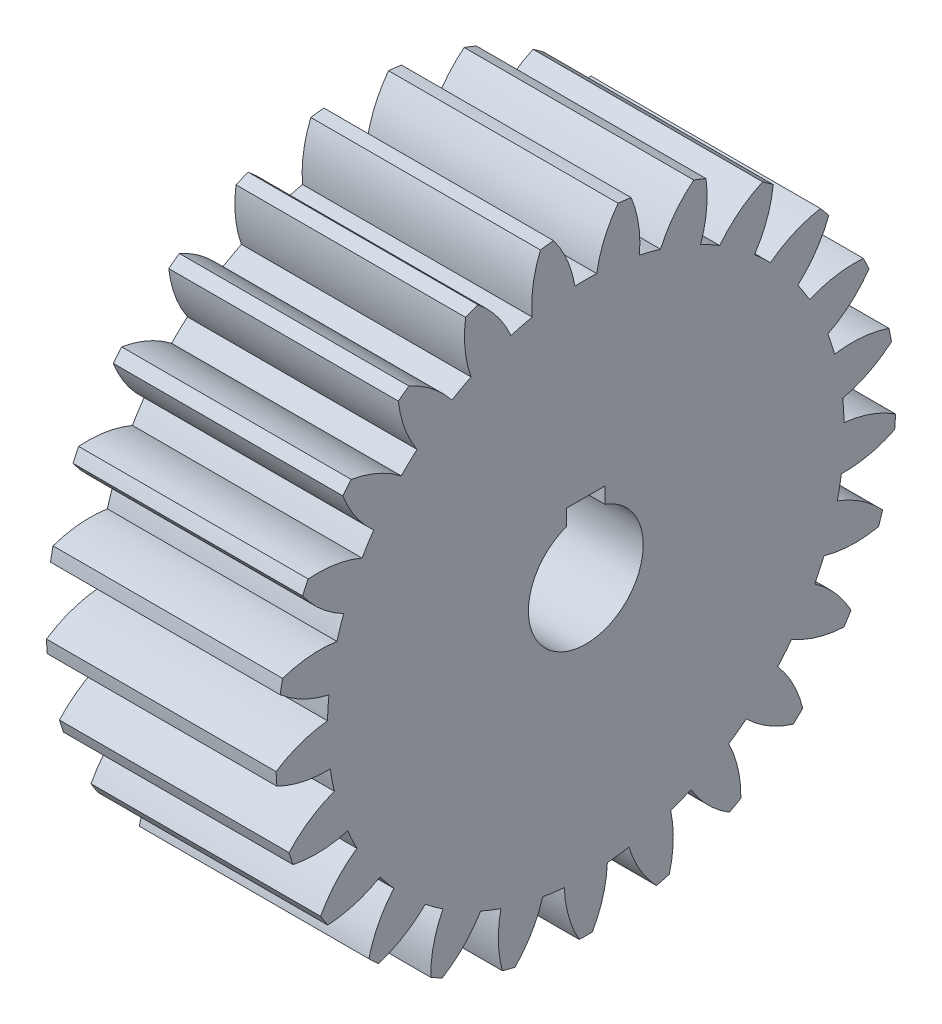
SolidWorks part; units mm, degrees
ref_plane "Plane1" through (0, 0, 0) normal (0, 0, 1) x (1, 0, 0)
ref_plane "Plane2" through (0, 0, 0) normal (0, 1, 0) x (1, 0, 0)
ref_plane "Plane3" through (0, 0, 0) normal (1, 0, 0) x (0, 0, -1)
other "Configuration Table"
sketch "HoldingSke" plane through (0, 0, 0) normal (0, 1, 0) x (1, 0, 0)
  line L0 (0, 0) -> (0.1511, -0.0704)
  line L1 (-15, 0) -> (100, 0) construction
  line L2 (0, 0) -> (-2.1039, 2.3779)
  line L3 (0, 0) -> (-11.863, 4.5341)
  line L4 (0, 0) -> (7.8269, 3.6497)
  line L5 (0, 0) -> (-46.8476, -17.4728)
  line L6 (0, 0) -> (-49.7378, -33.5582)
  line L7 (-2.1039, 2.3779) -> (10.8111, 60.9715)
  line L8 (-76.2, 54.61) -> (-72.9, 54.61)
  line L9 (-71.009, 38.7566) -> (-53.1078, 45.2721)
  line L10 (-76.2, 71.12) -> (104.1128, 71.12)
  line L11 (0, 0) -> (-60, 0)
  line L12 (-76.2, 101.6) -> (-75.993, 101.6)
  line L13 (24.9733, 27.94) -> (52.9518, 28.4284)
  line L14 (24.9733, 27.94) -> (24.9743, 27.94)
  line L15 (24.9733, 27.94) -> (100.4006, 29.5858)
  line L16 (-63.627, -6) -> (-12.827, -6)
  circle A0 centre (0, 0) radius 15
  circle A1 centre (0, 0) radius 37.5
  circle A2 centre (0, 0) radius 37.5
  circle A3 centre (0, 0) radius 15
  dimension "MHD" = 75
  dimension "Hub_dia" = 75
  dimension "Pitch" = 0.1667
  dimension "Overall_len" = 50
  dimension "Thickness" = 60
  dimension "OAL" = 60.0001
  dimension "T_dim" = 3.3
  dimension "Ap" = 20
  dimension "H" = 19.05
  dimension "Pitch_radius" = 180.3128
  dimension "Width" = 60
  dimension "Backlash" = 0.207
  dimension "Addendum_fac" = 1
  dimension "Dedendum_fac" = 1.25
  dimension "Clearance_fac" = 0.25
  dimension "Dedendum_add" = 0.001
  dimension "Module" = 6
sketch "BasProSke" plane through (0, 0, 0) normal (0, 1, 0) x (1, 0, 0)
  line L0 (-10, 0) -> (60, 0) construction
  line L1 (0, 0) -> (0, 81)
  line L2 (0, 0) -> (60, 0)
  line L3 (60, 0) -> (60, 81)
  line L4 (60, 81) -> (0, 81)
  dimension "Thickness" = 60
revolve "Base-Revolve" add sketch "BasProSke" angle 360 about L0
sketch "TooCutSke" plane through (0, 0, 0) normal (1, 0, 0) x (0, 0, -1)
  line L1 (0, 0) -> (0, 107) construction
  line L2 (0, 0) -> (-5.0714, 74.8283) construction
  line L3 (0, 0) -> (-18.7684, 148.567) construction
  line L4 (-5.0714, 74.8283) -> (-9.3842, 74.2835) construction
  arc A0 (2.8482, 67.4389) -> (-2.8482, 67.4389) centre (0, 0) ccw
  arc A1 (8.4641, 80.5821) -> (-8.4641, 80.5821) centre (0, 0) ccw
  circle A2 centre (0, 0) radius 75 construction
  circle A3 centre (0, 0) radius 70.4769 construction
  arc A4 (-2.8482, 67.4389) -> (-8.4641, 80.5821) centre (-32.4493, 62.5623) ccw
  arc A5 (8.4641, 80.5821) -> (2.8482, 67.4389) centre (32.4493, 62.5623) ccw
  dimension "Half_CT" = 4.347
extrude "ToothCut" cut sketch "TooCutSke" along normal through all
fillet "Breaks" [suppressed] radius 0.12
fillet "RootFillets" [suppressed] radius 1.501
pattern_circular "TeethCuts" count 25 every 14.4 about axis through (-10, 0, 0) along (1, 0, 0) of "ToothCut", "RootFillets", "Breaks"
sketch "HubNeaOneSke" plane through (0, 0, 0) normal (-1, 0, 0) x (0, 0, 1)
  circle A0 centre (0, 0) radius 37.5
  dimension "Diameter" = 75
extrude "HubNearOne" [suppressed] add sketch "HubNeaOneSke" along normal blind 10.0001
sketch "HubNeaBotSke" plane through (0, 0, 0) normal (-1, 0, 0) x (0, 0, 1)
  circle A0 centre (0, 0) radius 37.5
  dimension "Diameter" = 75
extrude "HubNearBoth" [suppressed] add sketch "HubNeaBotSke" along normal blind 5
ref_plane "FarPln" through (60, 0, 0) normal (1, 0, 0) x (0, 0, -1)
sketch "HubFarSke" plane through (60, 0, 0) normal (1, 0, 0) x (0, 0, -1)
  circle A0 centre (0, 0) radius 37.5
  dimension "Diameter" = 75
extrude "HubFar" [suppressed] add sketch "HubFarSke" along normal blind 5
sketch "BorSke" plane through (0, 0, 0) normal (1, 0, 0) x (0, 0, -1)
  circle A0 centre (0, 0) radius 15
extrude "Bore" cut sketch "BorSke" along normal mid plane 120.0001
sketch "KeySke" plane through (0, 0, 0) normal (1, 0, 0) x (0, 0, -1)
  line L0 (-5, 0) -> (-5, 18.3)
  line L1 (-5, 18.3) -> (5, 18.3)
  line L2 (5, 18.3) -> (5, 0)
  line L3 (0, 0) -> (0, 34) construction
  line L4 (-5, 0) -> (5, 0)
extrude "Keyway" cut sketch "KeySke" along normal mid plane 120.0001
pattern_circular "Keyway2" [suppressed] count 2 every 90 about axis through (-10, 0, 0) along (1, 0, 0)
equation "' \"Module@HoldingSke\" = 6.35"
equation "' \"Num_teeth@HoldingSke\" = 12"
equation "' \"Ap@HoldingSke\" =  20"
equation "' \"Ap@HoldingSke\" = 20"
equation "' \"Width@HoldingSke\" = 0.5 * 25.4"
equation "' \"Hub_dia@HoldingSke\"= 1 * 25.4"
equation "' \"Hub_dia@HoldingSke\" = 1 * 25.4"
equation "' \"Overall_len@HoldingSke\" = 1.0 * 25.4"
equation "' \"Bore@HoldingSke\" = 0.75 * 25.4"
equation "' \"T_dim@HoldingSke\" = 0.1 * 25.4"
equation "' \"Width@KeySke\" = 0.25 * 25.4"
equation "' \"Show_teeth@HoldingSke\" = 13"
equation "' \"Backlash@HoldingSke\" = 0.009 * 25.4"
equation "' \"Addendum_fac@HoldingSke\" = 1.0"
equation "' \"Dedendum_fac@HoldingSke\" = 1.25"
equation "' \"Dedendum_add@HoldingSke\" = 0.00005 * 25.4"
equation "' \"Clearance_fac@HoldingSke\" = 0.25"
equation "\"Pitch@HoldingSke\" = 1 / \"Module@HoldingSke\""
equation "\"Overcut_dia@TooCutSke\" = (\"Num_teeth@HoldingSke\" + 2 * \"Addendum_fac@HoldingSke\") / \"Pitch@HoldingSke\" + 0.002 * 25.4"
equation "\"Pitch_dia@TooCutSke\" = \"Num_teeth@HoldingSke\" / \"Pitch@HoldingSke\""
equation "\"Base_dia@TooCutSke\" = \"Num_teeth@HoldingSke\" / \"Pitch@HoldingSke\" * cos((\"Ap@HoldingSke\"  * 3.14159265 / 180))"
equation "\"Root_dia@TooCutSke\" = (\"Num_teeth@HoldingSke\" + 2) / \"Pitch@HoldingSke\" - 2 * (\"Addendum_fac@HoldingSke\" + \"Dedendum_fac@HoldingSke\") / \"Pitch@HoldingSke\" - \"Dedendum_add@HoldingSke\" * 2"
equation "\"Half_ang@TooCutSke\" = 180 / \"Num_teeth@HoldingSke\""
equation "\"Half_CT@TooCutSke\" = \"Num_teeth@HoldingSke\" / \"Pitch@HoldingSke\" * sin((3.14159265 / 2 / \"Num_teeth@HoldingSke\")) / 2 - 7 * \"Backlash@HoldingSke\" / 4"
equation "\"Flank_rad@TooCutSke\" = \"Num_teeth@HoldingSke\" / \"Pitch@HoldingSke\" / 5"
equation "\"Radius@RootFillets\" = \"Clearance_fac@HoldingSke\" / \"Pitch@HoldingSke\" + \"Dedendum_add@HoldingSke\""
equation "\"Break_rad@Breaks\" = 0.02 / \"Pitch@HoldingSke\""
equation "\"Thickness@HoldingSke\" = \"Width@HoldingSke\""
equation "\"OAL@HoldingSke\" = \"Thickness@HoldingSke\""
equation "\"MHD@HoldingSke\" = (\"Num_teeth@HoldingSke\" + 2) / \"Pitch@HoldingSke\" - 2 * (\"Addendum_fac@HoldingSke\" + \"Dedendum_fac@HoldingSke\")  / \"Pitch@HoldingSke\" - \"Dedendum_add@HoldingSke\" * 2"
equation "\"MBD@HoldingSke\" = (\"Num_teeth@HoldingSke\" + 2) / \"Pitch@HoldingSke\" - 2 * (\"Addendum_fac@HoldingSke\" + \"Dedendum_fac@HoldingSke\")  / \"Pitch@HoldingSke\" - \"Dedendum_add@HoldingSke\" * 2 - 0.002 * 25.4"
equation "\"MHD@HoldingSke\" = ((sgn( \"MHD@HoldingSke\" - \"Hub_dia@HoldingSke\" )-1)*( \"MHD@HoldingSke\" - \"Hub_dia@HoldingSke\" ))/-2+ \"Hub_dia@HoldingSke\""
equation "\"MBD@HoldingSke\" = ((sgn( \"MBD@HoldingSke\" - \"Bore@HoldingSke\" )-1)*( \"MBD@HoldingSke\" - \"Bore@HoldingSke\" ))/-2+ \"Bore@HoldingSke\""
equation "\"OAL@HoldingSke\" = ((sgn( \"OAL@HoldingSke\" - \"Overall_len@HoldingSke\" )+1)*( \"OAL@HoldingSke\" - \"Overall_len@HoldingSke\" ))/2 + \"Overall_len@HoldingSke\" + 0.000002 * 25.4"
equation "\"Num_teeth@TeethCuts\" = int( \"Show_teeth@HoldingSke\" ) + 1"
equation "\"Num_teeth@TeethCuts\" = ((sgn( \"Num_teeth@TeethCuts\" - \"Num_teeth@HoldingSke\" )-1)*( \"Num_teeth@TeethCuts\" - \"Num_teeth@HoldingSke\" ))/-2+ \"Num_teeth@HoldingSke\""
equation "\"Num_teeth@TeethCuts\" = ((sgn( \"Num_teeth@TeethCuts\" - 2.0)+1)*( \"Num_teeth@TeethCuts\" - 2.0))/2 +2.0"
equation "\"Angle@TeethCuts\" = 360.0 / \"Num_teeth@HoldingSke\""
equation "\"Diameter@BasProSke\" = (\"Num_teeth@HoldingSke\" + 2 * \"Addendum_fac@HoldingSke\") / \"Pitch@HoldingSke\""
equation "\"Thickness@BasProSke\"  = \"Thickness@HoldingSke\""
equation "' \"Fillet_rad@BasProSke\" =  \"Thickness@HoldingSke\" * 0.05"
equation "' \"Fillet_rad@BasProSke\" = \"Thickness@HoldingSke\" * 0.05"
equation "\"MHD@HoldingSke\" = ((sgn( \"MHD@HoldingSke\" - \"Root_dia@TooCutSke\" )-1)*( \"MHD@HoldingSke\" - \"Root_dia@TooCutSke\" ))/-2+ \"Root_dia@TooCutSke\""
equation "\"Diameter@HubNeaOneSke\" = \"MHD@HoldingSke\""
equation "\"Length@HubNearOne\" = \"OAL@HoldingSke\" - \"Thickness@BasProSke\""
equation "\"Diameter@HubNeaBotSke\" = \"MHD@HoldingSke\""
equation "\"Length@HubNearBoth\" = ( \"OAL@HoldingSke\" - \"Thickness@BasProSke\" ) / 2.0"
equation "\"Thickness@FarPln\" = \"Thickness@BasProSke\""
equation "\"Diameter@HubFarSke\" = \"MHD@HoldingSke\""
equation "\"Length@HubFar\" = ( \"OAL@HoldingSke\" - \"Thickness@BasProSke\" ) / 2.0"
equation "\"Diameter@BorSke\" = \"MBD@HoldingSke\""
equation "\"D1@Bore\" = \"OAL@HoldingSke\" * 2.0"
equation "\"D1@Keyway\" = \"OAL@HoldingSke\" * 2.0"
equation "\"Offset@KeySke\" = \"T_dim@HoldingSke\" + \"MBD@HoldingSke\" / 2.0"
